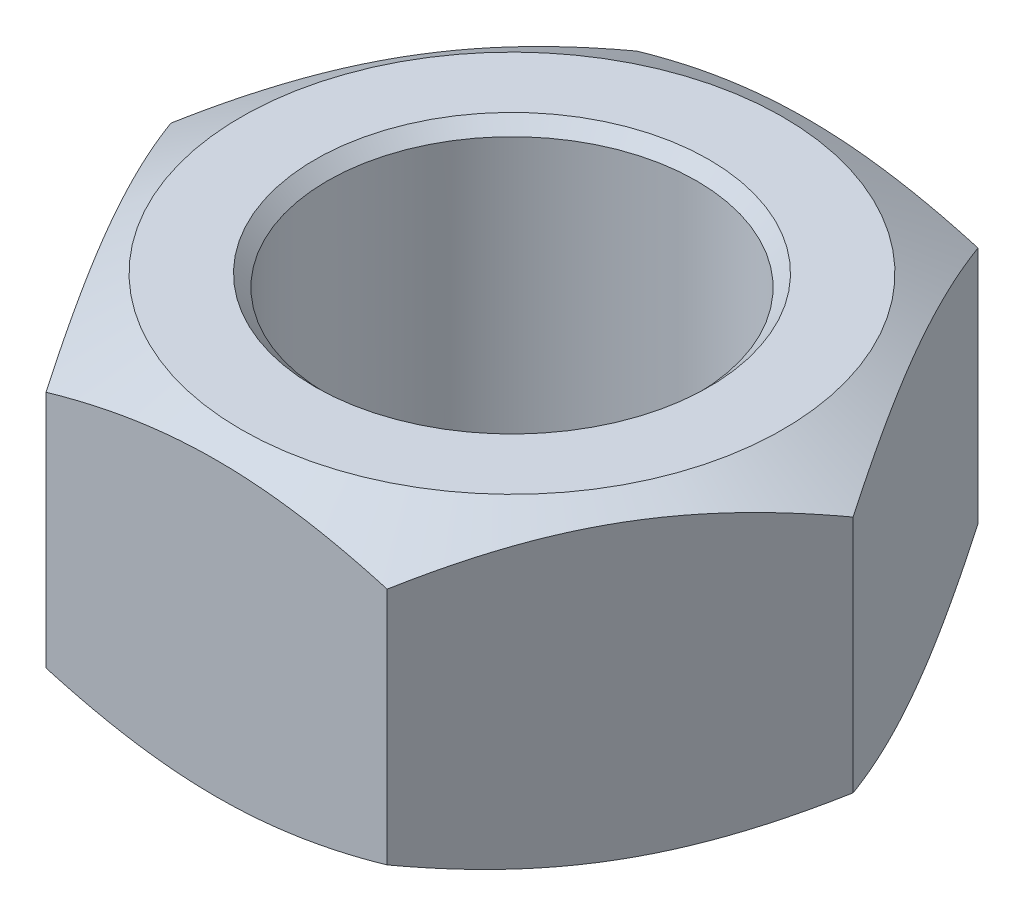
SolidWorks part; units mm, degrees
ref_plane "Спереди" through (0, 0, 0) normal (0, 0, 1) x (1, 0, 0)
ref_plane "Сверху" through (0, 0, 0) normal (0, 1, 0) x (1, 0, 0)
ref_plane "Справа" through (0, 0, 0) normal (1, 0, 0) x (0, 0, -1)
sketch "Эскиз1" plane through (0, 0, 0) normal (0, 1, 0) x (1, 0, 0)
  line L0 (-6.9282, 12) -> (6.9282, 12)
  line L1 (6.9282, 12) -> (13.8564, 0)
  line L2 (13.8564, 0) -> (6.9282, -12)
  line L3 (6.9282, -12) -> (-6.9282, -12)
  line L4 (-6.9282, -12) -> (-13.8564, 0)
  line L5 (-13.8564, 0) -> (-6.9282, 12)
  dimension "D5" = 12
  dimension "D2" = 120
  dimension "D3" = 120
  dimension "D4" = 120
  dimension "D6" = 12
  dimension "D7" = 12
  dimension "D8" = 12
  dimension "D9" = 12
  dimension "D10" = 120
  dimension "D11" = 12
extrude "Вытянуть1" add sketch "Эскиз1" against normal blind 13
sketch "Эскиз5" plane through (0, -13, 0) normal (0, -1, 0) x (1, 0, 0)
  circle A0 centre (0, 0) radius 7.5
  dimension "D1" = 15
extrude "Вырез-Вытянуть1" cut sketch "Эскиз5" against normal through all
ref_axis "Ось1" through (0, 0, 0) along (0, -1, 0)
ref_plane "Плоскость1" through (0, 0, 0) normal (0, 0, 1) x (1, 0, 0)
sketch "Эскиз4" plane through (0, 0, 0) normal (0, 0, 1) x (1, 0, 0)
  line L0 (-13.8564, -1.6491) -> (-11, 0)
  line L1 (-13.8564, -13) -> (-13.8564, 0) construction
  line L2 (-13.8564, 0) -> (-6.9282, 0) construction
  line L3 (-11, 0) -> (-13.8564, 0)
  line L4 (-13.8564, 0) -> (-13.8564, -1.6491)
  line L5 (-13.8564, -11.3509) -> (-11, -13)
  line L6 (-13.8564, -13) -> (-6.9282, -13) construction
  line L7 (-11, -13) -> (-13.8564, -13)
  line L8 (-13.8564, -13) -> (-13.8564, -11.3509)
  line L9 (0, 0) -> (0, -13) construction
  dimension "D1" = 11
  dimension "D2" = 30
  dimension "D3" = 11
  dimension "D4" = 30
revolve "Вырез-Повернуть1" cut sketch "Эскиз4" angle 360 about axis through (0, 0, 0) along (0, -1, 0)
chamfer "Фаска1" distance 0.5 angle 45 2 edges at (0, -13, -7.5) (0, 0, -7.5)
